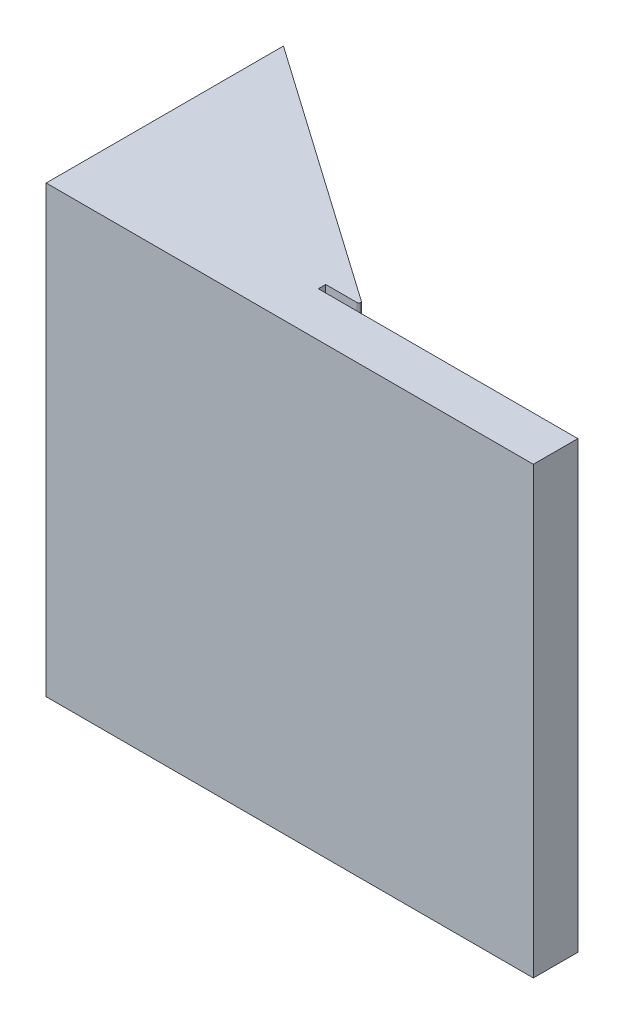
SolidWorks part; units mm, degrees
ref_plane "Front Plane" through (0, 0, 0) normal (0, 0, 1) x (1, 0, 0)
ref_plane "Top Plane" through (0, 0, 0) normal (0, 1, 0) x (1, 0, 0)
ref_plane "Right Plane" through (0, 0, 0) normal (1, 0, 0) x (0, 0, -1)
other "Configuration Table"
sketch "Sketch1" plane through (0, 0, 0) normal (0, 1, 0) x (1, 0, 0)
  line L0 (-15, 3) -> (-15, 4) construction
  line L5 (15, -3) -> (-15, -3)
  line L6 (15, -3) -> (15, 3)
  line L7 (15, 3) -> (-15, 3)
  line L8 (-15, -3) -> (-15, 3) construction
  line L9 (15, -3) -> (-15, 3) construction
  line L10 (15, 3) -> (-15, -3) construction
  line L11 (-50.7037, 29) -> (-50.7037, -3)
  line L12 (-50.7037, -3) -> (-15, -3)
  line L13 (-15, 4) -> (-50.7037, 4) construction
  line L14 (-15, 4) -> (-50.7037, 29)
  line L15 (-15, 4) -> (-20, 4)
  line L16 (-20, 4) -> (-20, 3)
  line L17 (-20, 3) -> (-15, 3)
  line L18 (-15.6913, 18) -> (-15.6913, 15) construction
  line L19 (-12.6913, 18) -> (41.3087, 18) construction
  line L20 (-15.6913, 15) -> (-15.6913, 6) construction
  line L21 (-12.6913, 3) -> (41.3087, 3) construction
  line L22 (44.3087, 15) -> (44.3087, 6) construction
  line L23 (-15.6913, 18) -> (44.3087, 3) construction
  line L24 (-15.6913, 3) -> (44.3087, 18) construction
  line L25 (-15.6913, 18) -> (-12.6913, 18) construction
  line L26 (41.3087, 18) -> (44.3087, 18) construction
  line L27 (44.3087, 18) -> (44.3087, 15) construction
  line L28 (42.2828, 8.8374) -> (44.3087, 3) construction
  line L29 (44.3087, 3) -> (41.3087, 3) construction
  line L30 (-12.6913, 3) -> (-15.6913, 3) construction
  line L31 (-15.6913, 3) -> (-15.6913, 6) construction
  arc A0 (41.3087, 3) -> (44.3087, 6) centre (41.3087, 6) ccw construction
  arc A1 (44.3087, 15) -> (41.3087, 18) centre (41.3087, 15) ccw construction
  arc A2 (-15.6913, 15) -> (-12.6913, 18) centre (-12.6913, 15) cw construction
  arc A3 (-15.6913, 6) -> (-12.6913, 3) centre (-12.6913, 6) ccw construction
  point P0 (0, 0)
  point P8 (-15.6439, 3.5)
  point P12 (14.3087, 10.5)
  point P31 (-12.8329, 19.445)
  point P32 (-15.6913, 3)
  dimension "D1" = 6
  dimension "D9" = 3
  dimension "D10" = 3
  dimension "D11" = 3
  dimension "D12" = 3
  dimension "D2" = 32
  dimension "D3" = 35
  dimension "D4" = 1
  dimension "D5" = 30
  dimension "D6" = 5
  dimension "D7" = 15
  dimension "D8" = 60
extrude "Boss-Extrude1" add sketch "Sketch1" along normal blind 60
fillet "Fillet1" radius 0.25 1 edges at (-15, 30, -4)
